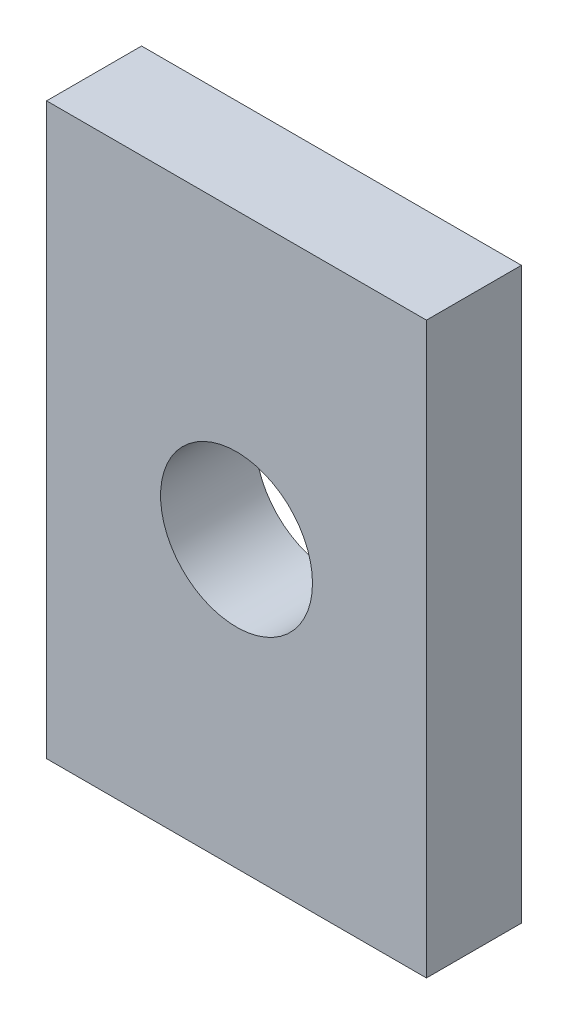
SolidWorks part; units mm, degrees
ref_plane "Front Plane" through (0, 0, 0) normal (0, 0, 1) x (1, 0, 0)
ref_plane "Top Plane" through (0, 0, 0) normal (0, 1, 0) x (1, 0, 0)
ref_plane "Right Plane" through (0, 0, 0) normal (1, 0, 0) x (0, 0, -1)
sketch "Sketch1" plane through (0, 0, 0) normal (0, 0, 1) x (1, 0, 0)
  line L1 (-10, 15) -> (10, 15)
  line L2 (-10, 15) -> (-10, -15)
  line L3 (-10, -15) -> (10, -15)
  line L4 (10, 15) -> (10, -15)
  dimension "D1" = 20
  dimension "D2" = 30
  dimension "D3" = 10
  dimension "D4" = 15
extrude "Boss-Extrude1" add sketch "Sketch1" along normal blind 5
sketch "Sketch2" plane through (0, 0, 5) normal (0, 0, 1) x (1, 0, 0)
  circle A0 centre (0, 0) radius 4
  dimension "D1" = 8
extrude "Cut-Extrude1" cut sketch "Sketch2" against normal blind 10
